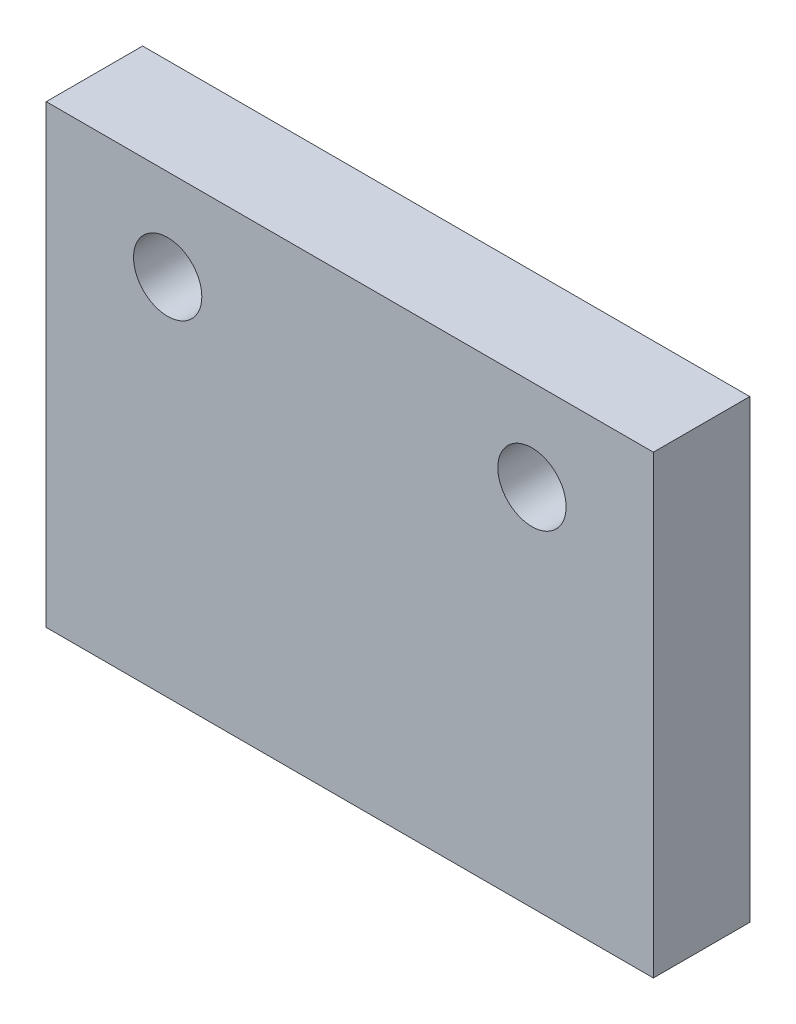
SolidWorks part; units mm, degrees
ref_plane "Front Plane" through (0, 0, 0) normal (0, 0, 1) x (1, 0, 0)
ref_plane "Top Plane" through (0, 0, 0) normal (0, 1, 0) x (1, 0, 0)
ref_plane "Right Plane" through (0, 0, 0) normal (1, 0, 0) x (0, 0, -1)
sketch "Sketch1" plane through (0, 0, 0) normal (0, 0, 1) x (1, 0, 0)
  line L1 (-20, -15) -> (20, -15)
  line L2 (-20, -15) -> (-20, 15)
  line L3 (-20, 15) -> (20, 15)
  line L4 (20, -15) -> (20, 15)
  line L5 (-20, -15) -> (20, 15) construction
  line L6 (-20, 15) -> (20, -15) construction
  circle A0 centre (-12, 9) radius 2.25
  circle A1 centre (12, 9) radius 2.25
  point P0 (0, 0)
  point P10 (0, 0)
  dimension "D1" = 24
  dimension "D4" = 4.5
  dimension "D2" = 8
  dimension "D3" = 30
extrude "Boss-Extrude1" add sketch "Sketch1" along normal blind 6.35
